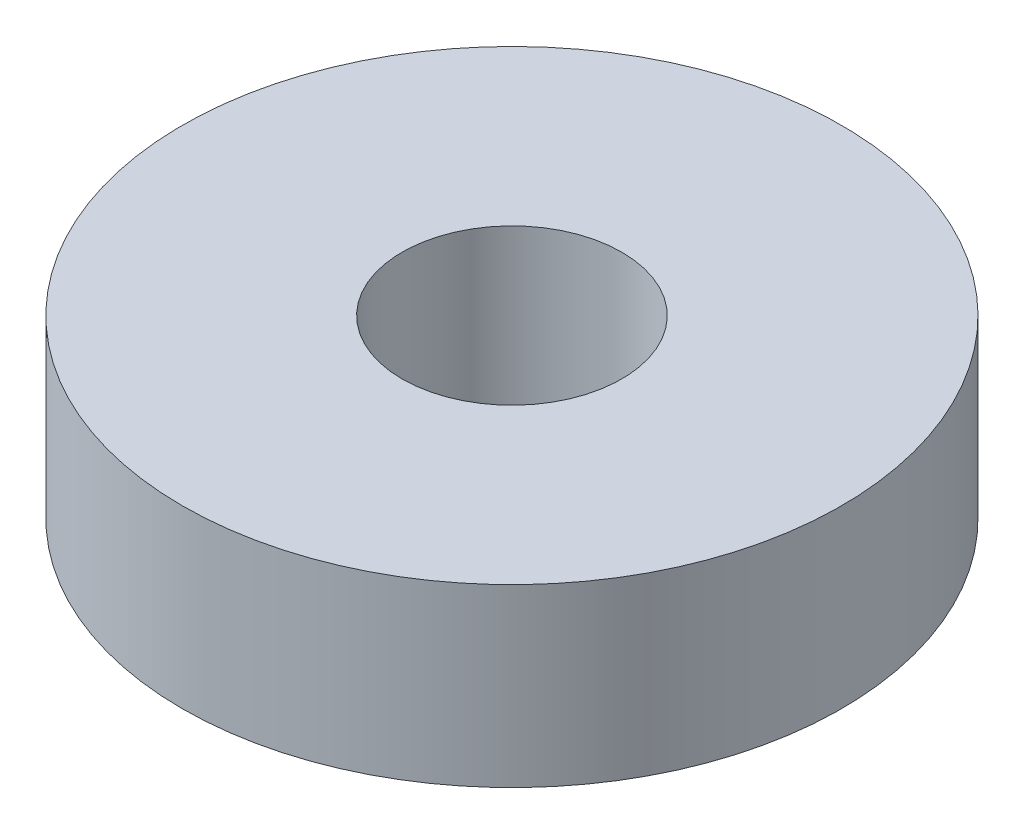
SolidWorks part; units mm, degrees
material "聚脂树脂"
ref_plane "前视基准面" through (0, 0, 0) normal (0, 0, 1) x (1, 0, 0)
ref_plane "上视基准面" through (0, 0, 0) normal (0, 1, 0) x (1, 0, 0)
ref_plane "右视基准面" through (0, 0, 0) normal (1, 0, 0) x (0, 0, -1)
other "Configuration Table"
sketch "草图1" plane through (0, 0, 0) normal (0, 1, 0) x (1, 0, 0)
  circle A0 centre (0, 0) radius 2.5
  circle A1 centre (0, 0) radius 7.5
  dimension "D1" = 5
  dimension "D2" = 15
extrude "凸台-拉伸1" add sketch "草图1" along normal blind 4
